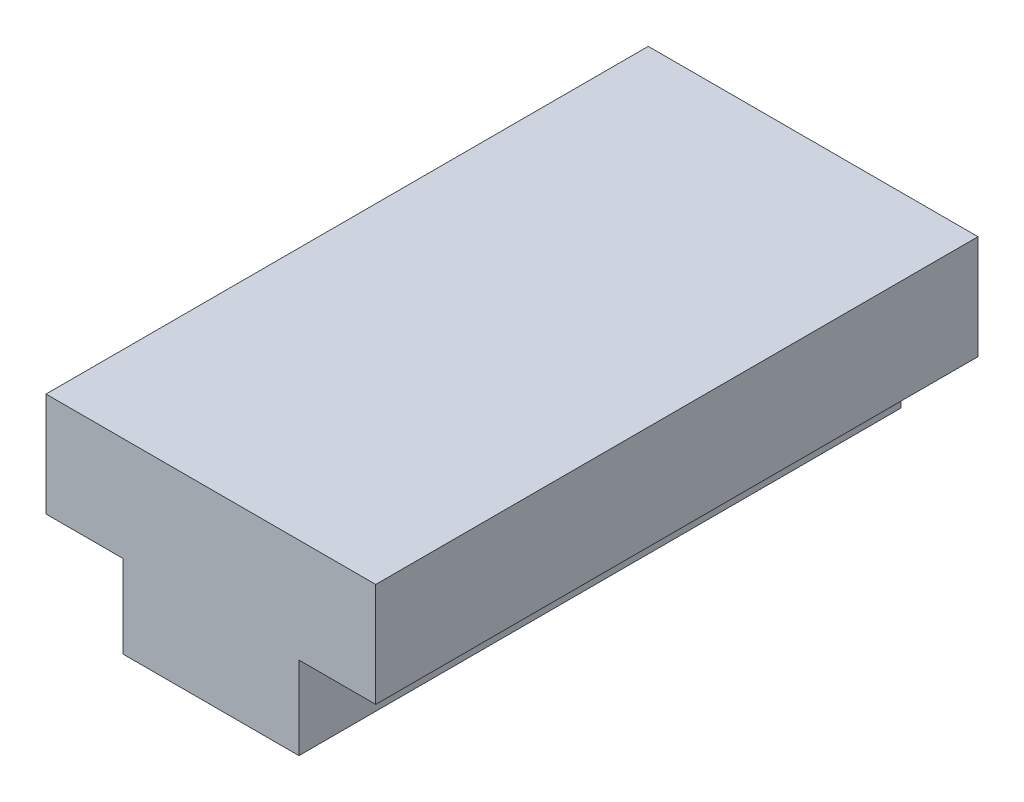
SolidWorks part; units mm, degrees
ref_plane "Спереди" through (0, 0, 0) normal (0, 0, 1) x (1, 0, 0)
ref_plane "Сверху" through (0, 0, 0) normal (0, 1, 0) x (1, 0, 0)
ref_plane "Справа" through (0, 0, 0) normal (1, 0, 0) x (0, 0, -1)
other "Configuration Table"
sketch "Sketch1" plane through (0, 0, 0) normal (0, 0, 1) x (1, 0, 0)
  line L0 (28.1483, 0) -> (5.85, 0) construction
  line L1 (0, -18.3368) -> (0, 18.3368) construction
  line L2 (-10.95, 0) -> (-5.85, 0)
  line L3 (10.95, 6.9) -> (-10.95, 6.9)
  line L4 (10.95, 6.9) -> (10.95, 0)
  line L5 (10.95, 0) -> (5.85, 0)
  line L6 (-10.95, 6.9) -> (-10.95, 0)
  line L7 (10.95, 6.9) -> (-10.95, 0) construction
  line L8 (10.95, 0) -> (-10.95, 6.9) construction
  line L9 (-5.85, 0) -> (-5.85, -5.5)
  line L10 (-5.85, -5.5) -> (5.85, -5.5)
  line L11 (5.85, 0) -> (5.85, -5.5)
  line L12 (-5.85, 0) -> (-28.1483, 0) construction
  line L13 (-5.85, 0) -> (-10.95, 0)
  point P0 (0, 3.45)
  point P4 (0, 0)
  point P8 (0, 0)
  point P16 (0, 0)
  point P17 (0, -5.5)
  point P18 (0, 0)
  point P19 (0, 0)
  point P20 (0, 0)
  dimension "D1" = 21.9
  dimension "D2" = 6.9
  dimension "D3" = 5.5
  dimension "D4" = 5.1
extrude "Boss-Extrude1" add sketch "Sketch1" against normal blind 40 contours L11 L5 L4 L3 L6 L2 L9 L10
